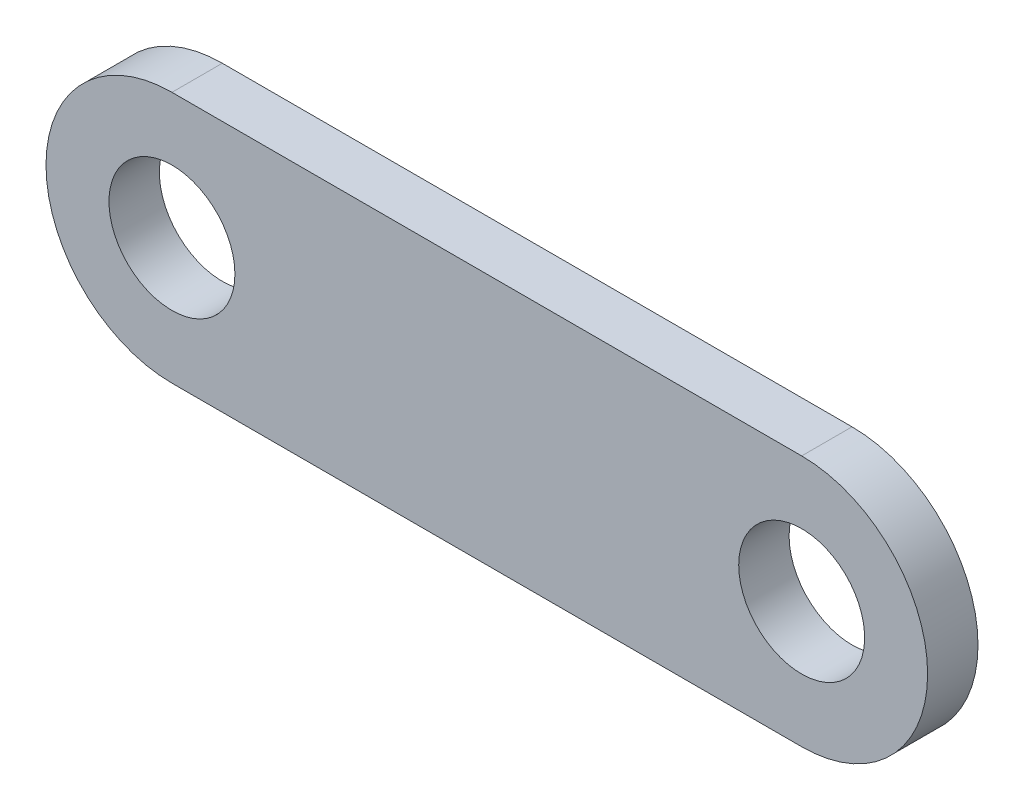
SolidWorks part; units mm, degrees
ref_plane "Front Plane" through (0, 0, 0) normal (0, 0, 1) x (1, 0, 0)
ref_plane "Top Plane" through (0, 0, 0) normal (0, 1, 0) x (1, 0, 0)
ref_plane "Right Plane" through (0, 0, 0) normal (1, 0, 0) x (0, 0, -1)
sketch "Sketch1" plane through (0, 0, 0) normal (0, 0, 1) x (1, 0, 0)
  line L0 (0, 0) -> (0, 141.7197) construction
  line L1 (125, -50) -> (-125, -50)
  line L3 (125, 50) -> (-125, 50)
  arc A0 (-125, -50) -> (-125, 50) centre (-125, 0) cw
  arc A1 (125, -50) -> (125, 50) centre (125, 0) ccw
  circle A2 centre (-125, 0) radius 25
  circle A3 centre (125, 0) radius 25
  point P0 (0, 0)
  dimension "D3" = 50
  dimension "D1" = 100
  dimension "D2" = 250
extrude "Boss-Extrude1" add sketch "Sketch1" along normal blind 20
